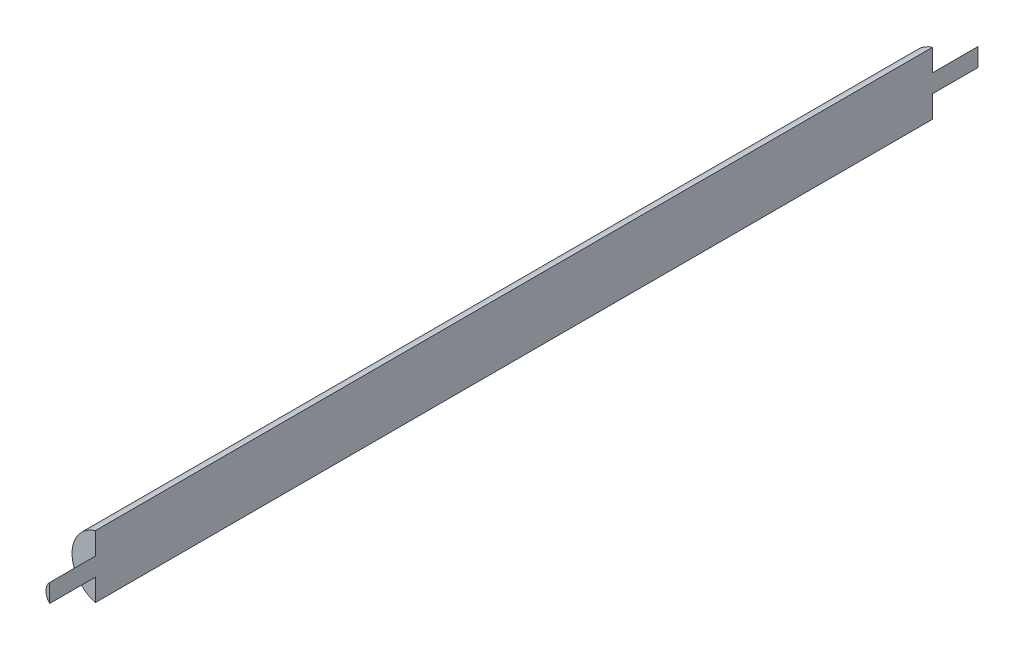
SolidWorks part; units mm, degrees
ref_plane "Ebene vorne" through (0, 0, 0) normal (0, 0, 1) x (1, 0, 0)
ref_plane "Ebene oben" through (0, 0, 0) normal (0, 1, 0) x (1, 0, 0)
ref_plane "Ebene rechts" through (0, 0, 0) normal (1, 0, 0) x (0, 0, -1)
sketch "Skizze1" plane through (0, 0, 0) normal (0, 0, 1) x (1, 0, 0)
  circle A0 centre (0, 0) radius 3.5
  dimension "D1" = 7
extrude "Aufsatz-Linear austragen1" add sketch "Skizze1" along normal blind 90
sketch "Skizze3" plane through (0, 0, 90) normal (0, 0, 1) x (1, 0, 0)
  circle A0 centre (0, 0) radius 1.4
  dimension "D1" = 2.8
sketch "Skizze4" plane through (0, 0, 0) normal (0, 0, -1) x (-1, 0, 0)
  circle A0 centre (0, 0) radius 1.4
  dimension "D1" = 2.8
extrude "Aufsatz-Linear austragen2" add sketch "Skizze3" along normal blind 4.9 contours A0
extrude "Aufsatz-Linear austragen3" add sketch "Skizze4" along normal blind 4.9
sketch "Skizze5" plane through (0, 0, 90) normal (0, 0, 1) x (1, 0, 0)
  line L0 (0, -3.5) -> (0, 3.5) construction
  line L2 (-1, 3.8684) -> (1, 3.8684)
  line L3 (-1, 3.8684) -> (-1, -4.1355)
  line L4 (-1, -4.1355) -> (1, -4.1355)
  line L5 (1, 3.8684) -> (1, -4.1355)
  circle A0 centre (0, 0) radius 3.5 construction
  dimension "D1" = 1
  dimension "D2" = 1
extrude "Schnitt-Linear austragen1" cut sketch "Skizze5" against normal through all and the other way through all
sketch "Skizze6" plane through (0, 0, 90) normal (0, 0, 1) x (1, 0, 0)
  line L1 (0.2041, 3.7981) -> (4.1304, 3.7981)
  line L2 (0.2041, 3.7981) -> (0.2041, -3.7179)
  line L3 (0.2041, -3.7179) -> (4.1304, -3.7179)
  line L4 (4.1304, 3.7981) -> (4.1304, -3.7179)
extrude "Schnitt-Linear austragen2" cut sketch "Skizze6" against normal through all and the other way through all
